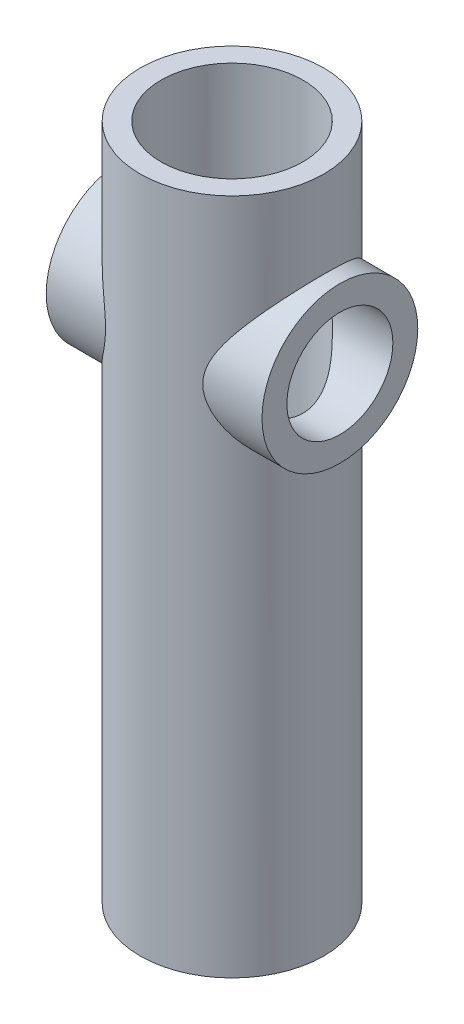
SolidWorks part; units mm, degrees
ref_plane "Front Plane" through (0, 0, 0) normal (0, 0, 1) x (1, 0, 0)
ref_plane "Top Plane" through (0, 0, 0) normal (0, 1, 0) x (1, 0, 0)
ref_plane "Right Plane" through (0, 0, 0) normal (1, 0, 0) x (0, 0, -1)
sketch "Sketch1" plane through (0, 0, 0) normal (1, 0, 0) x (0, 0, -1)
  circle A1 centre (0, 0) radius 32.766
  dimension "D2" = 65.532
extrude "Boss-Extrude1" add sketch "Sketch1" along normal blind 45.3728 and the other way blind 45.3883
sketch "Sketch2" plane through (0, 0, 0) normal (0, 1, 0) x (1, 0, 0)
  circle A0 centre (0, 0) radius 38.6334
  dimension "D1" = 77.2668
extrude "Boss-Extrude2" add sketch "Sketch2" along normal blind 69.2879 and the other way blind 215.6173
sketch "Sketch3" plane through (0, 0, 0) normal (1, 0, 0) x (0, 0, -1)
  circle A0 centre (0, 0) radius 22.2928
  dimension "D1" = 44.5856
extrude "Cut-Extrude1" cut sketch "Sketch3" against normal through all and the other way through all
sketch "Sketch4" plane through (0, 0, 0) normal (0, 1, 0) x (1, 0, 0)
  circle A1 centre (0, 0) radius 29.8403
  dimension "D2" = 59.6806
extrude "Cut-Extrude2" cut sketch "Sketch4" against normal blind 198.4197 and the other way through all
